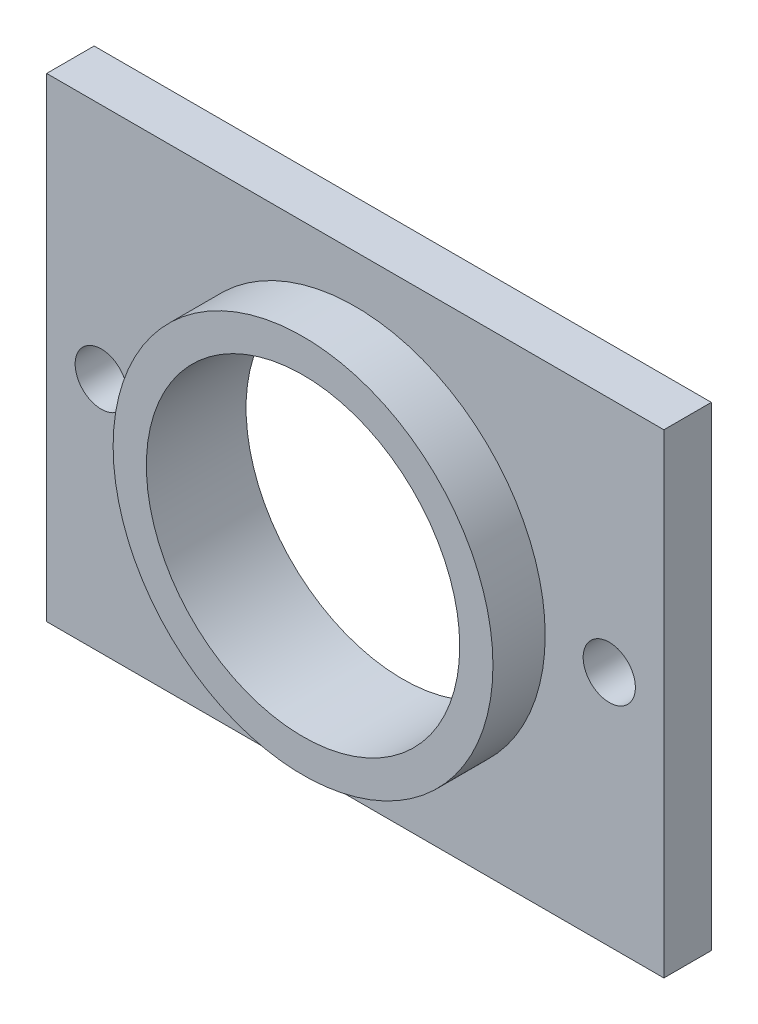
SolidWorks part; units mm, degrees
ref_plane "Front Plane" through (0, 0, 0) normal (0, 0, 1) x (1, 0, 0)
ref_plane "Top Plane" through (0, 0, 0) normal (0, 1, 0) x (1, 0, 0)
ref_plane "Right Plane" through (0, 0, 0) normal (1, 0, 0) x (0, 0, -1)
sketch "Cap_plate_26x20x2_Profile" plane through (0, 0, 0) normal (0, 0, 1) x (1, 0, 0)
  line L1 (-0.5, -10) -> (25.5, -10)
  line L2 (-0.5, -10) -> (-0.5, 10)
  line L3 (-0.5, 10) -> (25.5, 10)
  line L4 (25.5, -10) -> (25.5, 10)
  circle A0 centre (12.5, 0) radius 6.6
  circle A1 centre (1.8, 0) radius 1.1
  circle A2 centre (23.2, 0) radius 1.1
extrude "Cap_plate_26x20x2" add sketch "Cap_plate_26x20x2_Profile" along normal blind 2 from offset 12.4
sketch "Bearing_retention_lip_Profile" plane through (0, 0, 0) normal (0, 0, 1) x (1, 0, 0)
  circle A0 centre (12.5, 0) radius 8
  circle A1 centre (12.5, 0) radius 6.6
extrude "Bearing_retention_lip" add sketch "Bearing_retention_lip_Profile" along normal blind 2.21 from offset 10.41
